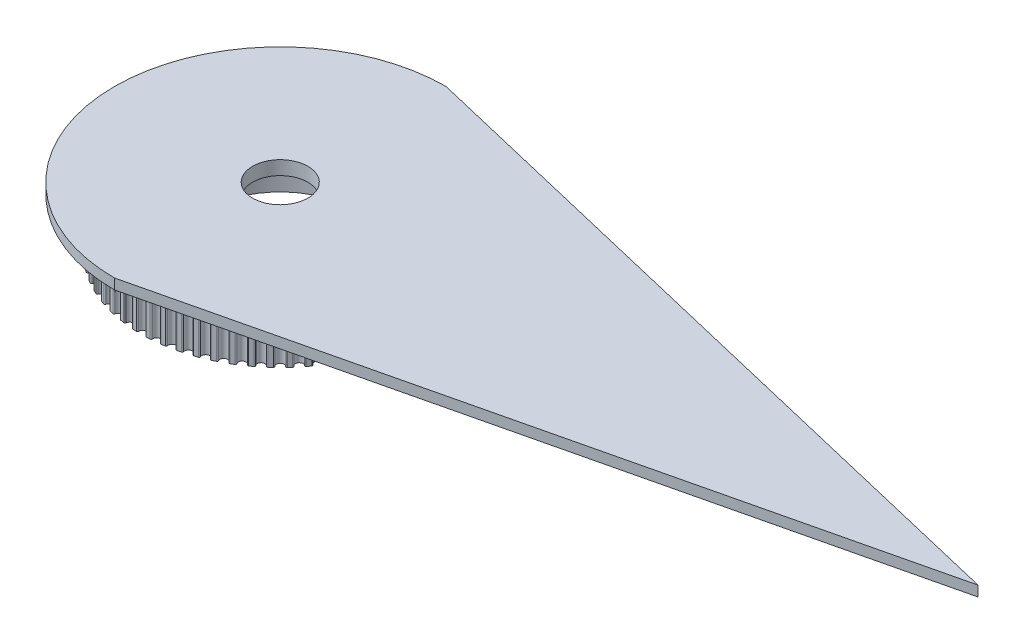
SolidWorks part; units mm, degrees
ref_plane "Front Plane" through (0, 0, 0) normal (0, 0, 1) x (1, 0, 0)
ref_plane "Top Plane" through (0, 0, 0) normal (0, 1, 0) x (1, 0, 0)
ref_plane "Right Plane" through (0, 0, 0) normal (1, 0, 0) x (0, 0, -1)
sketch "Sketch1" plane through (0, 0, 0) normal (0, 1, 0) x (1, 0, 0)
  line L2 (0, 24) -> (101, 0)
  line L3 (0, -24) -> (101, 0)
  arc A0 (0, 24) -> (0, -24) centre (0, 0) ccw
  point P5 (0, -12)
  dimension "D1" = 24
  dimension "D2" = 101
extrude "Boss-Extrude1" add sketch "Sketch1" along normal blind 1.5
sketch "Sketch2" plane through (0, 0, 0) normal (0, -1, 0) x (1, 0, 0)
  line L0 (0, 0) -> (0, 11) construction
  line L2 (0, 0) -> (1.0782, 10.947) construction
  circle A1 centre (0, 0) radius 11
  arc A3 (0, 19.37) -> (0.5544, 19.9506) centre (0, 19.925) ccw
  arc A4 (1.4038, 19.9089) -> (1.8986, 19.2767) centre (1.953, 19.8291) ccw
  arc A5 (0.7095, 20.1075) -> (0.5544, 19.9506) centre (0.7042, 19.9576) ccw
  arc A6 (1.4038, 19.9089) -> (1.2648, 20.0802) centre (1.2553, 19.9305) ccw
  arc A7 (1.2648, 20.0802) -> (0.7095, 20.1075) centre (0, 0) ccw
  arc A8 (1.8986, 19.2767) -> (2.5072, 19.8002) centre (1.953, 19.8291) ccw
  arc A9 (3.2269, 19.8595) -> (2.677, 19.9411) centre (0, 0) ccw
  arc A10 (3.3484, 19.6755) -> (3.7789, 18.9978) centre (3.8872, 19.5421) ccw
  arc A11 (3.3484, 19.6755) -> (3.2269, 19.8595) centre (3.2028, 19.7115) ccw
  arc A12 (2.677, 19.9411) -> (2.5072, 19.8002) centre (2.657, 19.7924) ccw
  arc A13 (3.7789, 18.9978) -> (4.4359, 19.4591) centre (3.8872, 19.5421) ccw
  arc A14 (5.1579, 19.4476) -> (4.6187, 19.5827) centre (0, 0) ccw
  arc A15 (5.2608, 19.2525) -> (5.6228, 18.5359) centre (5.7839, 19.067) ccw
  arc A16 (5.2608, 19.2525) -> (5.1579, 19.4476) centre (5.1195, 19.3026) ccw
  arc A17 (4.6187, 19.5827) -> (4.4359, 19.4591) centre (4.5842, 19.4367) ccw
  arc A18 (5.6228, 18.5359) -> (6.3219, 18.9306) centre (5.7839, 19.067) ccw
  arc A19 (7.0393, 18.8484) -> (6.5159, 19.0357) centre (0, 0) ccw
  arc A20 (7.1226, 18.6442) -> (7.4126, 17.8955) centre (7.625, 18.4083) ccw
  arc A21 (7.1226, 18.6442) -> (7.0393, 18.8484) centre (6.9868, 18.7079) ccw
  arc A22 (6.5159, 19.0357) -> (6.3219, 18.9306) centre (6.4673, 18.8938) ccw
  arc A23 (7.4126, 17.8955) -> (8.147, 18.2198) centre (7.625, 18.4083) ccw
  arc A24 (8.8528, 18.0677) -> (8.3503, 18.3054) centre (0, 0) ccw
  arc A25 (8.9157, 17.8562) -> (9.131, 17.0828) centre (9.3926, 17.5723) ccw
  arc A26 (8.9157, 17.8562) -> (8.8528, 18.0677) centre (8.7868, 17.933) ccw
  arc A27 (8.3503, 18.3054) -> (8.147, 18.2198) centre (8.2881, 18.1689) ccw
  arc A28 (9.131, 17.0828) -> (9.8936, 17.3336) centre (9.3926, 17.5723) ccw
  arc A29 (10.5812, 17.113) -> (10.1044, 17.3987) centre (0, 0) ccw
  arc A30 (10.623, 16.8964) -> (10.7614, 16.1056) centre (11.0697, 16.567) ccw
  arc A31 (10.623, 16.8964) -> (10.5812, 17.113) centre (10.5023, 16.9854) ccw
  arc A32 (10.1044, 17.3987) -> (9.8936, 17.3336) centre (10.029, 17.269) ccw
  arc A33 (10.7614, 16.1056) -> (11.545, 16.2803) centre (11.0697, 16.567) ccw
  arc A34 (12.2076, 15.9934) -> (11.7611, 16.3246) centre (0, 0) ccw
  arc A35 (12.228, 15.7738) -> (12.2882, 14.9732) centre (12.6403, 15.4022) ccw
  arc A36 (12.228, 15.7738) -> (12.2076, 15.9934) centre (12.1166, 15.8742) ccw
  arc A37 (11.7611, 16.3246) -> (11.545, 16.2803) centre (11.6734, 16.2029) ccw
  arc A38 (12.2882, 14.9732) -> (13.0851, 15.0703) centre (12.6403, 15.4022) ccw
  arc A39 (13.7164, 14.7199) -> (13.3045, 15.0932) centre (0, 0) ccw
  arc A40 (13.7152, 14.4993) -> (13.6967, 13.6967) centre (14.0891, 14.0891) ccw
  arc A41 (13.7152, 14.4993) -> (13.7164, 14.7199) centre (13.6142, 14.6101) ccw
  arc A42 (13.3045, 15.0932) -> (13.0851, 15.0703) centre (13.2053, 14.9806) ccw
  arc A43 (13.6967, 13.6967) -> (14.4993, 13.7152) centre (14.0891, 14.0891) ccw
  arc A44 (15.0932, 13.3045) -> (14.7199, 13.7164) centre (0, 0) ccw
  arc A45 (15.0703, 13.0851) -> (14.9732, 12.2882) centre (15.4022, 12.6403) ccw
  arc A46 (15.0703, 13.0851) -> (15.0932, 13.3045) centre (14.9806, 13.2053) ccw
  arc A47 (14.7199, 13.7164) -> (14.4993, 13.7152) centre (14.6101, 13.6142) ccw
  arc A48 (14.9732, 12.2882) -> (15.7738, 12.228) centre (15.4022, 12.6403) ccw
  arc A49 (16.3246, 11.7611) -> (15.9934, 12.2076) centre (0, 0) ccw
  arc A50 (16.2803, 11.545) -> (16.1056, 10.7614) centre (16.567, 11.0697) ccw
  arc A51 (16.2803, 11.545) -> (16.3246, 11.7611) centre (16.2029, 11.6734) ccw
  arc A52 (15.9934, 12.2076) -> (15.7738, 12.228) centre (15.8742, 12.1166) ccw
  arc A53 (16.1056, 10.7614) -> (16.8964, 10.623) centre (16.567, 11.0697) ccw
  arc A54 (17.3987, 10.1044) -> (17.113, 10.5812) centre (0, 0) ccw
  arc A55 (17.3336, 9.8936) -> (17.0828, 9.131) centre (17.5723, 9.3926) ccw
  arc A56 (17.3336, 9.8936) -> (17.3987, 10.1044) centre (17.269, 10.029) ccw
  arc A57 (17.113, 10.5812) -> (16.8964, 10.623) centre (16.9854, 10.5023) ccw
  arc A58 (17.0828, 9.131) -> (17.8562, 8.9157) centre (17.5723, 9.3926) ccw
  arc A59 (18.3054, 8.3503) -> (18.0677, 8.8528) centre (0, 0) ccw
  arc A60 (18.2198, 8.147) -> (17.8955, 7.4126) centre (18.4083, 7.625) ccw
  arc A61 (18.2198, 8.147) -> (18.3054, 8.3503) centre (18.1689, 8.2881) ccw
  arc A62 (18.0677, 8.8528) -> (17.8562, 8.9157) centre (17.933, 8.7868) ccw
  arc A63 (17.8955, 7.4126) -> (18.6442, 7.1226) centre (18.4083, 7.625) ccw
  arc A64 (19.0357, 6.5159) -> (18.8484, 7.0393) centre (0, 0) ccw
  arc A65 (18.9306, 6.3219) -> (18.5359, 5.6228) centre (19.067, 5.7839) ccw
  arc A66 (18.9306, 6.3219) -> (19.0357, 6.5159) centre (18.8938, 6.4673) ccw
  arc A67 (18.8484, 7.0393) -> (18.6442, 7.1226) centre (18.7079, 6.9868) ccw
  arc A68 (18.5359, 5.6228) -> (19.2525, 5.2608) centre (19.067, 5.7839) ccw
  arc A69 (19.5827, 4.6187) -> (19.4476, 5.1579) centre (0, 0) ccw
  arc A70 (19.4591, 4.4359) -> (18.9978, 3.7789) centre (19.5421, 3.8872) ccw
  arc A71 (19.4591, 4.4359) -> (19.5827, 4.6187) centre (19.4367, 4.5842) ccw
  arc A72 (19.4476, 5.1579) -> (19.2525, 5.2608) centre (19.3026, 5.1195) ccw
  arc A73 (18.9978, 3.7789) -> (19.6755, 3.3484) centre (19.5421, 3.8872) ccw
  arc A74 (19.9411, 2.677) -> (19.8595, 3.2269) centre (0, 0) ccw
  arc A75 (19.8002, 2.5072) -> (19.2767, 1.8986) centre (19.8291, 1.953) ccw
  arc A76 (19.8002, 2.5072) -> (19.9411, 2.677) centre (19.7924, 2.657) ccw
  arc A77 (19.8595, 3.2269) -> (19.6755, 3.3484) centre (19.7115, 3.2028) ccw
  arc A78 (19.2767, 1.8986) -> (19.9089, 1.4038) centre (19.8291, 1.953) ccw
  arc A79 (20.1075, 0.7095) -> (20.0802, 1.2648) centre (0, 0) ccw
  arc A80 (19.9506, 0.5544) -> (19.37, 0) centre (19.925, 0) ccw
  arc A81 (19.9506, 0.5544) -> (20.1075, 0.7095) centre (19.9576, 0.7042) ccw
  arc A82 (20.0802, 1.2648) -> (19.9089, 1.4038) centre (19.9305, 1.2553) ccw
  arc A83 (19.37, 0) -> (19.9506, -0.5544) centre (19.925, 0) ccw
  arc A84 (20.0802, -1.2648) -> (20.1075, -0.7095) centre (0, 0) ccw
  arc A85 (19.9089, -1.4038) -> (19.2767, -1.8986) centre (19.8291, -1.953) ccw
  arc A86 (19.9089, -1.4038) -> (20.0802, -1.2648) centre (19.9305, -1.2553) ccw
  arc A87 (20.1075, -0.7095) -> (19.9506, -0.5544) centre (19.9576, -0.7042) ccw
  arc A88 (19.2767, -1.8986) -> (19.8002, -2.5072) centre (19.8291, -1.953) ccw
  arc A89 (19.8595, -3.2269) -> (19.9411, -2.677) centre (0, 0) ccw
  arc A90 (19.6755, -3.3484) -> (18.9978, -3.7789) centre (19.5421, -3.8872) ccw
  arc A91 (19.6755, -3.3484) -> (19.8595, -3.2269) centre (19.7115, -3.2028) ccw
  arc A92 (19.9411, -2.677) -> (19.8002, -2.5072) centre (19.7924, -2.657) ccw
  arc A93 (18.9978, -3.7789) -> (19.4591, -4.4359) centre (19.5421, -3.8872) ccw
  arc A94 (19.4476, -5.1579) -> (19.5827, -4.6187) centre (0, 0) ccw
  arc A95 (19.2525, -5.2608) -> (18.5359, -5.6228) centre (19.067, -5.7839) ccw
  arc A96 (19.2525, -5.2608) -> (19.4476, -5.1579) centre (19.3026, -5.1195) ccw
  arc A97 (19.5827, -4.6187) -> (19.4591, -4.4359) centre (19.4367, -4.5842) ccw
  arc A98 (18.5359, -5.6228) -> (18.9306, -6.3219) centre (19.067, -5.7839) ccw
  arc A99 (18.8484, -7.0393) -> (19.0357, -6.5159) centre (0, 0) ccw
  arc A100 (18.6442, -7.1226) -> (17.8955, -7.4126) centre (18.4083, -7.625) ccw
  arc A101 (18.6442, -7.1226) -> (18.8484, -7.0393) centre (18.7079, -6.9868) ccw
  arc A102 (19.0357, -6.5159) -> (18.9306, -6.3219) centre (18.8938, -6.4673) ccw
  arc A103 (17.8955, -7.4126) -> (18.2198, -8.147) centre (18.4083, -7.625) ccw
  arc A104 (18.0677, -8.8528) -> (18.3054, -8.3503) centre (0, 0) ccw
  arc A105 (17.8562, -8.9157) -> (17.0828, -9.131) centre (17.5723, -9.3926) ccw
  arc A106 (17.8562, -8.9157) -> (18.0677, -8.8528) centre (17.933, -8.7868) ccw
  arc A107 (18.3054, -8.3503) -> (18.2198, -8.147) centre (18.1689, -8.2881) ccw
  arc A108 (17.0828, -9.131) -> (17.3336, -9.8936) centre (17.5723, -9.3926) ccw
  arc A109 (17.113, -10.5812) -> (17.3987, -10.1044) centre (0, 0) ccw
  arc A110 (16.8964, -10.623) -> (16.1056, -10.7614) centre (16.567, -11.0697) ccw
  arc A111 (16.8964, -10.623) -> (17.113, -10.5812) centre (16.9854, -10.5023) ccw
  arc A112 (17.3987, -10.1044) -> (17.3336, -9.8936) centre (17.269, -10.029) ccw
  arc A113 (16.1056, -10.7614) -> (16.2803, -11.545) centre (16.567, -11.0697) ccw
  arc A114 (15.9934, -12.2076) -> (16.3246, -11.7611) centre (0, 0) ccw
  arc A115 (15.7738, -12.228) -> (14.9732, -12.2882) centre (15.4022, -12.6403) ccw
  arc A116 (15.7738, -12.228) -> (15.9934, -12.2076) centre (15.8742, -12.1166) ccw
  arc A117 (16.3246, -11.7611) -> (16.2803, -11.545) centre (16.2029, -11.6734) ccw
  arc A118 (14.9732, -12.2882) -> (15.0703, -13.0851) centre (15.4022, -12.6403) ccw
  arc A119 (14.7199, -13.7164) -> (15.0932, -13.3045) centre (0, 0) ccw
  arc A120 (14.4993, -13.7152) -> (13.6967, -13.6967) centre (14.0891, -14.0891) ccw
  arc A121 (14.4993, -13.7152) -> (14.7199, -13.7164) centre (14.6101, -13.6142) ccw
  arc A122 (15.0932, -13.3045) -> (15.0703, -13.0851) centre (14.9806, -13.2053) ccw
  arc A123 (13.6967, -13.6967) -> (13.7152, -14.4993) centre (14.0891, -14.0891) ccw
  arc A124 (13.3045, -15.0932) -> (13.7164, -14.7199) centre (0, 0) ccw
  arc A125 (13.0851, -15.0703) -> (12.2882, -14.9732) centre (12.6403, -15.4022) ccw
  arc A126 (13.0851, -15.0703) -> (13.3045, -15.0932) centre (13.2053, -14.9806) ccw
  arc A127 (13.7164, -14.7199) -> (13.7152, -14.4993) centre (13.6142, -14.6101) ccw
  arc A128 (12.2882, -14.9732) -> (12.228, -15.7738) centre (12.6403, -15.4022) ccw
  arc A129 (11.7611, -16.3246) -> (12.2076, -15.9934) centre (0, 0) ccw
  arc A130 (11.545, -16.2803) -> (10.7614, -16.1056) centre (11.0697, -16.567) ccw
  arc A131 (11.545, -16.2803) -> (11.7611, -16.3246) centre (11.6734, -16.2029) ccw
  arc A132 (12.2076, -15.9934) -> (12.228, -15.7738) centre (12.1166, -15.8742) ccw
  arc A133 (10.7614, -16.1056) -> (10.623, -16.8964) centre (11.0697, -16.567) ccw
  arc A134 (10.1044, -17.3987) -> (10.5812, -17.113) centre (0, 0) ccw
  arc A135 (9.8936, -17.3336) -> (9.131, -17.0828) centre (9.3926, -17.5723) ccw
  arc A136 (9.8936, -17.3336) -> (10.1044, -17.3987) centre (10.029, -17.269) ccw
  arc A137 (10.5812, -17.113) -> (10.623, -16.8964) centre (10.5023, -16.9854) ccw
  arc A138 (9.131, -17.0828) -> (8.9157, -17.8562) centre (9.3926, -17.5723) ccw
  arc A139 (8.3503, -18.3054) -> (8.8528, -18.0677) centre (0, 0) ccw
  arc A140 (8.147, -18.2198) -> (7.4126, -17.8955) centre (7.625, -18.4083) ccw
  arc A141 (8.147, -18.2198) -> (8.3503, -18.3054) centre (8.2881, -18.1689) ccw
  arc A142 (8.8528, -18.0677) -> (8.9157, -17.8562) centre (8.7868, -17.933) ccw
  arc A143 (7.4126, -17.8955) -> (7.1226, -18.6442) centre (7.625, -18.4083) ccw
  arc A144 (6.5159, -19.0357) -> (7.0393, -18.8484) centre (0, 0) ccw
  arc A145 (6.3219, -18.9306) -> (5.6228, -18.5359) centre (5.7839, -19.067) ccw
  arc A146 (6.3219, -18.9306) -> (6.5159, -19.0357) centre (6.4673, -18.8938) ccw
  arc A147 (7.0393, -18.8484) -> (7.1226, -18.6442) centre (6.9868, -18.7079) ccw
  arc A148 (5.6228, -18.5359) -> (5.2608, -19.2525) centre (5.7839, -19.067) ccw
  arc A149 (4.6187, -19.5827) -> (5.1579, -19.4476) centre (0, 0) ccw
  arc A150 (4.4359, -19.4591) -> (3.7789, -18.9978) centre (3.8872, -19.5421) ccw
  arc A151 (4.4359, -19.4591) -> (4.6187, -19.5827) centre (4.5842, -19.4367) ccw
  arc A152 (5.1579, -19.4476) -> (5.2608, -19.2525) centre (5.1195, -19.3026) ccw
  arc A153 (3.7789, -18.9978) -> (3.3484, -19.6755) centre (3.8872, -19.5421) ccw
  arc A154 (2.677, -19.9411) -> (3.2269, -19.8595) centre (0, 0) ccw
  arc A155 (2.5072, -19.8002) -> (1.8986, -19.2767) centre (1.953, -19.8291) ccw
  arc A156 (2.5072, -19.8002) -> (2.677, -19.9411) centre (2.657, -19.7924) ccw
  arc A157 (3.2269, -19.8595) -> (3.3484, -19.6755) centre (3.2028, -19.7115) ccw
  arc A158 (1.8986, -19.2767) -> (1.4038, -19.9089) centre (1.953, -19.8291) ccw
  arc A159 (0.7095, -20.1075) -> (1.2648, -20.0802) centre (0, 0) ccw
  arc A160 (0.5544, -19.9506) -> (0, -19.37) centre (0, -19.925) ccw
  arc A161 (0.5544, -19.9506) -> (0.7095, -20.1075) centre (0.7042, -19.9576) ccw
  arc A162 (1.2648, -20.0802) -> (1.4038, -19.9089) centre (1.2553, -19.9305) ccw
  arc A163 (0, -19.37) -> (-0.5544, -19.9506) centre (0, -19.925) ccw
  arc A164 (-1.2648, -20.0802) -> (-0.7095, -20.1075) centre (0, 0) ccw
  arc A165 (-1.4038, -19.9089) -> (-1.8986, -19.2767) centre (-1.953, -19.8291) ccw
  arc A166 (-1.4038, -19.9089) -> (-1.2648, -20.0802) centre (-1.2553, -19.9305) ccw
  arc A167 (-0.7095, -20.1075) -> (-0.5544, -19.9506) centre (-0.7042, -19.9576) ccw
  arc A168 (-1.8986, -19.2767) -> (-2.5072, -19.8002) centre (-1.953, -19.8291) ccw
  arc A169 (-3.2269, -19.8595) -> (-2.677, -19.9411) centre (0, 0) ccw
  arc A170 (-3.3484, -19.6755) -> (-3.7789, -18.9978) centre (-3.8872, -19.5421) ccw
  arc A171 (-3.3484, -19.6755) -> (-3.2269, -19.8595) centre (-3.2028, -19.7115) ccw
  arc A172 (-2.677, -19.9411) -> (-2.5072, -19.8002) centre (-2.657, -19.7924) ccw
  arc A173 (-3.7789, -18.9978) -> (-4.4359, -19.4591) centre (-3.8872, -19.5421) ccw
  arc A174 (-5.1579, -19.4476) -> (-4.6187, -19.5827) centre (0, 0) ccw
  arc A175 (-5.2608, -19.2525) -> (-5.6228, -18.5359) centre (-5.7839, -19.067) ccw
  arc A176 (-5.2608, -19.2525) -> (-5.1579, -19.4476) centre (-5.1195, -19.3026) ccw
  arc A177 (-4.6187, -19.5827) -> (-4.4359, -19.4591) centre (-4.5842, -19.4367) ccw
  arc A178 (-5.6228, -18.5359) -> (-6.3219, -18.9306) centre (-5.7839, -19.067) ccw
  arc A179 (-7.0393, -18.8484) -> (-6.5159, -19.0357) centre (0, 0) ccw
  arc A180 (-7.1226, -18.6442) -> (-7.4126, -17.8955) centre (-7.625, -18.4083) ccw
  arc A181 (-7.1226, -18.6442) -> (-7.0393, -18.8484) centre (-6.9868, -18.7079) ccw
  arc A182 (-6.5159, -19.0357) -> (-6.3219, -18.9306) centre (-6.4673, -18.8938) ccw
  arc A183 (-7.4126, -17.8955) -> (-8.147, -18.2198) centre (-7.625, -18.4083) ccw
  arc A184 (-8.8528, -18.0677) -> (-8.3503, -18.3054) centre (0, 0) ccw
  arc A185 (-8.9157, -17.8562) -> (-9.131, -17.0828) centre (-9.3926, -17.5723) ccw
  arc A186 (-8.9157, -17.8562) -> (-8.8528, -18.0677) centre (-8.7868, -17.933) ccw
  arc A187 (-8.3503, -18.3054) -> (-8.147, -18.2198) centre (-8.2881, -18.1689) ccw
  arc A188 (-9.131, -17.0828) -> (-9.8936, -17.3336) centre (-9.3926, -17.5723) ccw
  arc A189 (-10.5812, -17.113) -> (-10.1044, -17.3987) centre (0, 0) ccw
  arc A190 (-10.623, -16.8964) -> (-10.7614, -16.1056) centre (-11.0697, -16.567) ccw
  arc A191 (-10.623, -16.8964) -> (-10.5812, -17.113) centre (-10.5023, -16.9854) ccw
  arc A192 (-10.1044, -17.3987) -> (-9.8936, -17.3336) centre (-10.029, -17.269) ccw
  arc A193 (-10.7614, -16.1056) -> (-11.545, -16.2803) centre (-11.0697, -16.567) ccw
  arc A194 (-12.2076, -15.9934) -> (-11.7611, -16.3246) centre (0, 0) ccw
  arc A195 (-12.228, -15.7738) -> (-12.2882, -14.9732) centre (-12.6403, -15.4022) ccw
  arc A196 (-12.228, -15.7738) -> (-12.2076, -15.9934) centre (-12.1166, -15.8742) ccw
  arc A197 (-11.7611, -16.3246) -> (-11.545, -16.2803) centre (-11.6734, -16.2029) ccw
  arc A198 (-12.2882, -14.9732) -> (-13.0851, -15.0703) centre (-12.6403, -15.4022) ccw
  arc A199 (-13.7164, -14.7199) -> (-13.3045, -15.0932) centre (0, 0) ccw
  arc A200 (-13.7152, -14.4993) -> (-13.6967, -13.6967) centre (-14.0891, -14.0891) ccw
  arc A201 (-13.7152, -14.4993) -> (-13.7164, -14.7199) centre (-13.6142, -14.6101) ccw
  arc A202 (-13.3045, -15.0932) -> (-13.0851, -15.0703) centre (-13.2053, -14.9806) ccw
  arc A203 (-13.6967, -13.6967) -> (-14.4993, -13.7152) centre (-14.0891, -14.0891) ccw
  arc A204 (-15.0932, -13.3045) -> (-14.7199, -13.7164) centre (0, 0) ccw
  arc A205 (-15.0703, -13.0851) -> (-14.9732, -12.2882) centre (-15.4022, -12.6403) ccw
  arc A206 (-15.0703, -13.0851) -> (-15.0932, -13.3045) centre (-14.9806, -13.2053) ccw
  arc A207 (-14.7199, -13.7164) -> (-14.4993, -13.7152) centre (-14.6101, -13.6142) ccw
  arc A208 (-14.9732, -12.2882) -> (-15.7738, -12.228) centre (-15.4022, -12.6403) ccw
  arc A209 (-16.3246, -11.7611) -> (-15.9934, -12.2076) centre (0, 0) ccw
  arc A210 (-16.2803, -11.545) -> (-16.1056, -10.7614) centre (-16.567, -11.0697) ccw
  arc A211 (-16.2803, -11.545) -> (-16.3246, -11.7611) centre (-16.2029, -11.6734) ccw
  arc A212 (-15.9934, -12.2076) -> (-15.7738, -12.228) centre (-15.8742, -12.1166) ccw
  arc A213 (-16.1056, -10.7614) -> (-16.8964, -10.623) centre (-16.567, -11.0697) ccw
  arc A214 (-17.3987, -10.1044) -> (-17.113, -10.5812) centre (0, 0) ccw
  arc A215 (-17.3336, -9.8936) -> (-17.0828, -9.131) centre (-17.5723, -9.3926) ccw
  arc A216 (-17.3336, -9.8936) -> (-17.3987, -10.1044) centre (-17.269, -10.029) ccw
  arc A217 (-17.113, -10.5812) -> (-16.8964, -10.623) centre (-16.9854, -10.5023) ccw
  arc A218 (-17.0828, -9.131) -> (-17.8562, -8.9157) centre (-17.5723, -9.3926) ccw
  arc A219 (-18.3054, -8.3503) -> (-18.0677, -8.8528) centre (0, 0) ccw
  arc A220 (-18.2198, -8.147) -> (-17.8955, -7.4126) centre (-18.4083, -7.625) ccw
  arc A221 (-18.2198, -8.147) -> (-18.3054, -8.3503) centre (-18.1689, -8.2881) ccw
  arc A222 (-18.0677, -8.8528) -> (-17.8562, -8.9157) centre (-17.933, -8.7868) ccw
  arc A223 (-17.8955, -7.4126) -> (-18.6442, -7.1226) centre (-18.4083, -7.625) ccw
  arc A224 (-19.0357, -6.5159) -> (-18.8484, -7.0393) centre (0, 0) ccw
  arc A225 (-18.9306, -6.3219) -> (-18.5359, -5.6228) centre (-19.067, -5.7839) ccw
  arc A226 (-18.9306, -6.3219) -> (-19.0357, -6.5159) centre (-18.8938, -6.4673) ccw
  arc A227 (-18.8484, -7.0393) -> (-18.6442, -7.1226) centre (-18.7079, -6.9868) ccw
  arc A228 (-18.5359, -5.6228) -> (-19.2525, -5.2608) centre (-19.067, -5.7839) ccw
  arc A229 (-19.5827, -4.6187) -> (-19.4476, -5.1579) centre (0, 0) ccw
  arc A230 (-19.4591, -4.4359) -> (-18.9978, -3.7789) centre (-19.5421, -3.8872) ccw
  arc A231 (-19.4591, -4.4359) -> (-19.5827, -4.6187) centre (-19.4367, -4.5842) ccw
  arc A232 (-19.4476, -5.1579) -> (-19.2525, -5.2608) centre (-19.3026, -5.1195) ccw
  arc A233 (-18.9978, -3.7789) -> (-19.6755, -3.3484) centre (-19.5421, -3.8872) ccw
  arc A234 (-19.9411, -2.677) -> (-19.8595, -3.2269) centre (0, 0) ccw
  arc A235 (-19.8002, -2.5072) -> (-19.2767, -1.8986) centre (-19.8291, -1.953) ccw
  arc A236 (-19.8002, -2.5072) -> (-19.9411, -2.677) centre (-19.7924, -2.657) ccw
  arc A237 (-19.8595, -3.2269) -> (-19.6755, -3.3484) centre (-19.7115, -3.2028) ccw
  arc A238 (-19.2767, -1.8986) -> (-19.9089, -1.4038) centre (-19.8291, -1.953) ccw
  arc A239 (-20.1075, -0.7095) -> (-20.0802, -1.2648) centre (0, 0) ccw
  arc A240 (-19.9506, -0.5544) -> (-19.37, 0) centre (-19.925, 0) ccw
  arc A241 (-19.9506, -0.5544) -> (-20.1075, -0.7095) centre (-19.9576, -0.7042) ccw
  arc A242 (-20.0802, -1.2648) -> (-19.9089, -1.4038) centre (-19.9305, -1.2553) ccw
  arc A243 (-19.37, 0) -> (-19.9506, 0.5544) centre (-19.925, 0) ccw
  arc A244 (-20.0802, 1.2648) -> (-20.1075, 0.7095) centre (0, 0) ccw
  arc A245 (-19.9089, 1.4038) -> (-19.2767, 1.8986) centre (-19.8291, 1.953) ccw
  arc A246 (-19.9089, 1.4038) -> (-20.0802, 1.2648) centre (-19.9305, 1.2553) ccw
  arc A247 (-20.1075, 0.7095) -> (-19.9506, 0.5544) centre (-19.9576, 0.7042) ccw
  arc A248 (-19.2767, 1.8986) -> (-19.8002, 2.5072) centre (-19.8291, 1.953) ccw
  arc A249 (-19.8595, 3.2269) -> (-19.9411, 2.677) centre (0, 0) ccw
  arc A250 (-19.6755, 3.3484) -> (-18.9978, 3.7789) centre (-19.5421, 3.8872) ccw
  arc A251 (-19.6755, 3.3484) -> (-19.8595, 3.2269) centre (-19.7115, 3.2028) ccw
  arc A252 (-19.9411, 2.677) -> (-19.8002, 2.5072) centre (-19.7924, 2.657) ccw
  arc A253 (-18.9978, 3.7789) -> (-19.4591, 4.4359) centre (-19.5421, 3.8872) ccw
  arc A254 (-19.4476, 5.1579) -> (-19.5827, 4.6187) centre (0, 0) ccw
  arc A255 (-19.2525, 5.2608) -> (-18.5359, 5.6228) centre (-19.067, 5.7839) ccw
  arc A256 (-19.2525, 5.2608) -> (-19.4476, 5.1579) centre (-19.3026, 5.1195) ccw
  arc A257 (-19.5827, 4.6187) -> (-19.4591, 4.4359) centre (-19.4367, 4.5842) ccw
  arc A258 (-18.5359, 5.6228) -> (-18.9306, 6.3219) centre (-19.067, 5.7839) ccw
  arc A259 (-18.8484, 7.0393) -> (-19.0357, 6.5159) centre (0, 0) ccw
  arc A260 (-18.6442, 7.1226) -> (-17.8955, 7.4126) centre (-18.4083, 7.625) ccw
  arc A261 (-18.6442, 7.1226) -> (-18.8484, 7.0393) centre (-18.7079, 6.9868) ccw
  arc A262 (-19.0357, 6.5159) -> (-18.9306, 6.3219) centre (-18.8938, 6.4673) ccw
  arc A263 (-17.8955, 7.4126) -> (-18.2198, 8.147) centre (-18.4083, 7.625) ccw
  arc A264 (-18.0677, 8.8528) -> (-18.3054, 8.3503) centre (0, 0) ccw
  arc A265 (-17.8562, 8.9157) -> (-17.0828, 9.131) centre (-17.5723, 9.3926) ccw
  arc A266 (-17.8562, 8.9157) -> (-18.0677, 8.8528) centre (-17.933, 8.7868) ccw
  arc A267 (-18.3054, 8.3503) -> (-18.2198, 8.147) centre (-18.1689, 8.2881) ccw
  arc A268 (-17.0828, 9.131) -> (-17.3336, 9.8936) centre (-17.5723, 9.3926) ccw
  arc A269 (-17.113, 10.5812) -> (-17.3987, 10.1044) centre (0, 0) ccw
  arc A270 (-16.8964, 10.623) -> (-16.1056, 10.7614) centre (-16.567, 11.0697) ccw
  arc A271 (-16.8964, 10.623) -> (-17.113, 10.5812) centre (-16.9854, 10.5023) ccw
  arc A272 (-17.3987, 10.1044) -> (-17.3336, 9.8936) centre (-17.269, 10.029) ccw
  arc A273 (-16.1056, 10.7614) -> (-16.2803, 11.545) centre (-16.567, 11.0697) ccw
  arc A274 (-15.9934, 12.2076) -> (-16.3246, 11.7611) centre (0, 0) ccw
  arc A275 (-15.7738, 12.228) -> (-14.9732, 12.2882) centre (-15.4022, 12.6403) ccw
  arc A276 (-15.7738, 12.228) -> (-15.9934, 12.2076) centre (-15.8742, 12.1166) ccw
  arc A277 (-16.3246, 11.7611) -> (-16.2803, 11.545) centre (-16.2029, 11.6734) ccw
  arc A278 (-14.9732, 12.2882) -> (-15.0703, 13.0851) centre (-15.4022, 12.6403) ccw
  arc A279 (-14.7199, 13.7164) -> (-15.0932, 13.3045) centre (0, 0) ccw
  arc A280 (-14.4993, 13.7152) -> (-13.6967, 13.6967) centre (-14.0891, 14.0891) ccw
  arc A281 (-14.4993, 13.7152) -> (-14.7199, 13.7164) centre (-14.6101, 13.6142) ccw
  arc A282 (-15.0932, 13.3045) -> (-15.0703, 13.0851) centre (-14.9806, 13.2053) ccw
  arc A283 (-13.6967, 13.6967) -> (-13.7152, 14.4993) centre (-14.0891, 14.0891) ccw
  arc A284 (-13.3045, 15.0932) -> (-13.7164, 14.7199) centre (0, 0) ccw
  arc A285 (-13.0851, 15.0703) -> (-12.2882, 14.9732) centre (-12.6403, 15.4022) ccw
  arc A286 (-13.0851, 15.0703) -> (-13.3045, 15.0932) centre (-13.2053, 14.9806) ccw
  arc A287 (-13.7164, 14.7199) -> (-13.7152, 14.4993) centre (-13.6142, 14.6101) ccw
  arc A288 (-12.2882, 14.9732) -> (-12.228, 15.7738) centre (-12.6403, 15.4022) ccw
  arc A289 (-11.7611, 16.3246) -> (-12.2076, 15.9934) centre (0, 0) ccw
  arc A290 (-11.545, 16.2803) -> (-10.7614, 16.1056) centre (-11.0697, 16.567) ccw
  arc A291 (-11.545, 16.2803) -> (-11.7611, 16.3246) centre (-11.6734, 16.2029) ccw
  arc A292 (-12.2076, 15.9934) -> (-12.228, 15.7738) centre (-12.1166, 15.8742) ccw
  arc A293 (-10.7614, 16.1056) -> (-10.623, 16.8964) centre (-11.0697, 16.567) ccw
  arc A294 (-10.1044, 17.3987) -> (-10.5812, 17.113) centre (0, 0) ccw
  arc A295 (-9.8936, 17.3336) -> (-9.131, 17.0828) centre (-9.3926, 17.5723) ccw
  arc A296 (-9.8936, 17.3336) -> (-10.1044, 17.3987) centre (-10.029, 17.269) ccw
  arc A297 (-10.5812, 17.113) -> (-10.623, 16.8964) centre (-10.5023, 16.9854) ccw
  arc A298 (-9.131, 17.0828) -> (-8.9157, 17.8562) centre (-9.3926, 17.5723) ccw
  arc A299 (-8.3503, 18.3054) -> (-8.8528, 18.0677) centre (0, 0) ccw
  arc A300 (-8.147, 18.2198) -> (-7.4126, 17.8955) centre (-7.625, 18.4083) ccw
  arc A301 (-8.147, 18.2198) -> (-8.3503, 18.3054) centre (-8.2881, 18.1689) ccw
  arc A302 (-8.8528, 18.0677) -> (-8.9157, 17.8562) centre (-8.7868, 17.933) ccw
  arc A303 (-7.4126, 17.8955) -> (-7.1226, 18.6442) centre (-7.625, 18.4083) ccw
  arc A304 (-6.5159, 19.0357) -> (-7.0393, 18.8484) centre (0, 0) ccw
  arc A305 (-6.3219, 18.9306) -> (-5.6228, 18.5359) centre (-5.7839, 19.067) ccw
  arc A306 (-6.3219, 18.9306) -> (-6.5159, 19.0357) centre (-6.4673, 18.8938) ccw
  arc A307 (-7.0393, 18.8484) -> (-7.1226, 18.6442) centre (-6.9868, 18.7079) ccw
  arc A308 (-5.6228, 18.5359) -> (-5.2608, 19.2525) centre (-5.7839, 19.067) ccw
  arc A309 (-4.6187, 19.5827) -> (-5.1579, 19.4476) centre (0, 0) ccw
  arc A310 (-4.4359, 19.4591) -> (-3.7789, 18.9978) centre (-3.8872, 19.5421) ccw
  arc A311 (-4.4359, 19.4591) -> (-4.6187, 19.5827) centre (-4.5842, 19.4367) ccw
  arc A312 (-5.1579, 19.4476) -> (-5.2608, 19.2525) centre (-5.1195, 19.3026) ccw
  arc A313 (-3.7789, 18.9978) -> (-3.3484, 19.6755) centre (-3.8872, 19.5421) ccw
  arc A314 (-2.677, 19.9411) -> (-3.2269, 19.8595) centre (0, 0) ccw
  arc A315 (-2.5072, 19.8002) -> (-1.8986, 19.2767) centre (-1.953, 19.8291) ccw
  arc A316 (-2.5072, 19.8002) -> (-2.677, 19.9411) centre (-2.657, 19.7924) ccw
  arc A317 (-3.2269, 19.8595) -> (-3.3484, 19.6755) centre (-3.2028, 19.7115) ccw
  arc A318 (-1.8986, 19.2767) -> (-1.4038, 19.9089) centre (-1.953, 19.8291) ccw
  arc A319 (-0.7095, 20.1075) -> (-1.2648, 20.0802) centre (0, 0) ccw
  arc A320 (-0.5544, 19.9506) -> (0, 19.37) centre (0, 19.925) ccw
  arc A321 (-0.5544, 19.9506) -> (-0.7095, 20.1075) centre (-0.7042, 19.9576) ccw
  arc A322 (-1.2648, 20.0802) -> (-1.4038, 19.9089) centre (-1.2553, 19.9305) ccw
  point P650 (0, 0)
  dimension "D2" = 64
  dimension "D4" = 1.11
  dimension "D5" = 1.11
  dimension "D6" = 0.3
  dimension "D7" = 0.3
extrude "Boss-Extrude3" add sketch "Sketch2" along normal blind 7.5
sketch "Sketch3" plane through (0, 0, 0) normal (0, -1, 0) x (1, 0, 0)
  circle A0 centre (0, 0) radius 6
  circle A1 centre (0, 0) radius 4
extrude "Boss-Extrude4" add sketch "Sketch3" along normal blind 0.5
sketch "Sketch4" plane through (0, 0, 0) normal (0, -1, 0) x (-1, 0, 0)
  circle A0 centre (0, 0) radius 4
extrude "Cut-Extrude1" cut sketch "Sketch4" against normal through all
